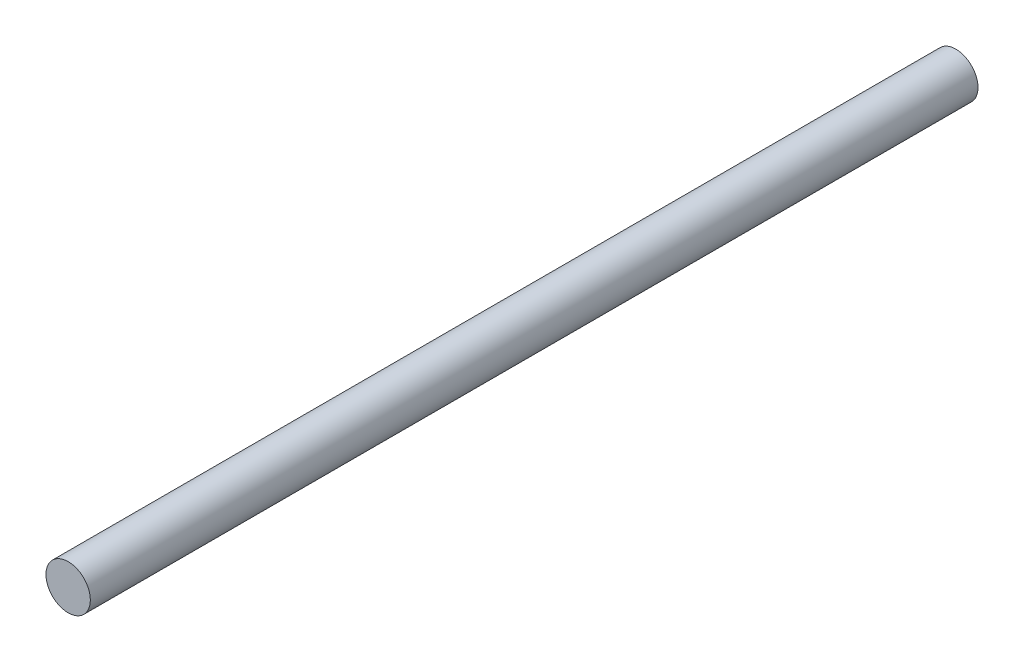
SolidWorks part; units mm, degrees
material "Oak"
ref_plane "Front Plane" through (0, 0, 0) normal (0, 0, 1) x (1, 0, 0)
ref_plane "Top Plane" through (0, 0, 0) normal (0, 1, 0) x (1, 0, 0)
ref_plane "Right Plane" through (0, 0, 0) normal (1, 0, 0) x (0, 0, -1)
sketch "Sketch1" plane through (0, 0, 0) normal (0, 0, 1) x (1, 0, 0)
  circle A0 centre (0, 0) radius 10
extrude "Boss-Extrude1" add sketch "Sketch1" along normal blind 400
